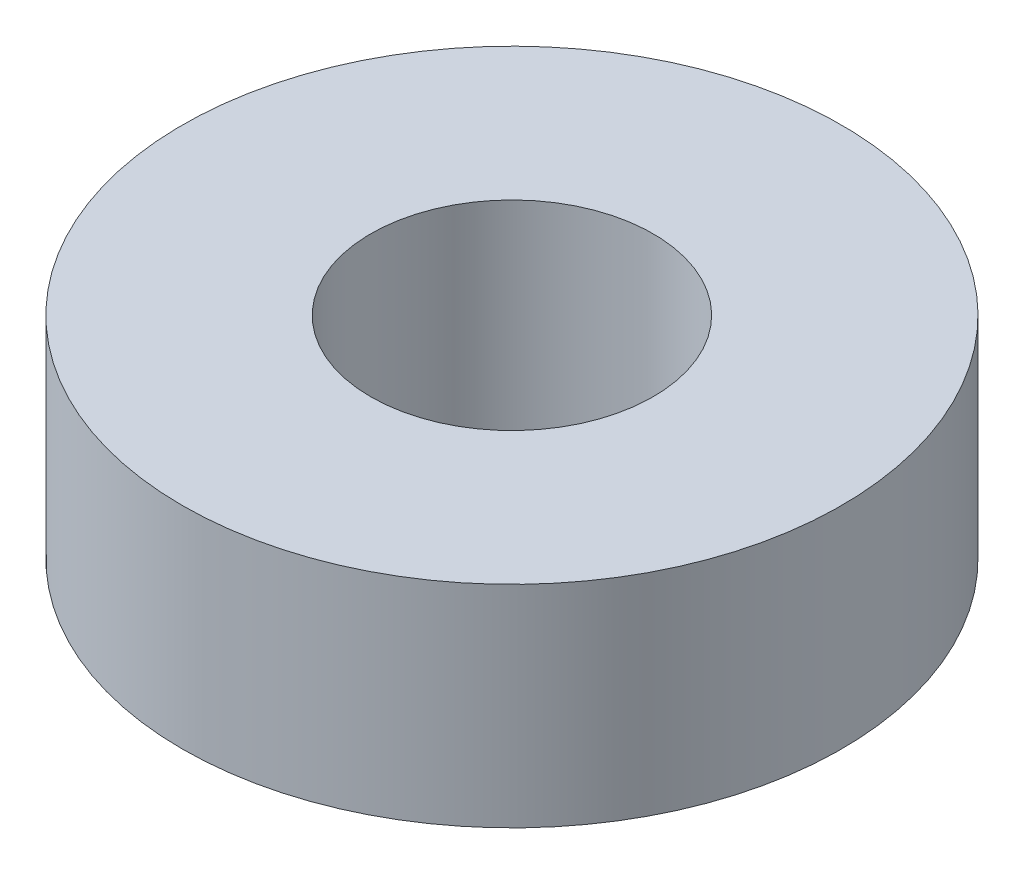
SolidWorks part; units mm, degrees
ref_plane "Front Plane" through (0, 0, 0) normal (0, 0, 1) x (1, 0, 0)
ref_plane "Top Plane" through (0, 0, 0) normal (0, 1, 0) x (1, 0, 0)
ref_plane "Right Plane" through (0, 0, 0) normal (1, 0, 0) x (0, 0, -1)
sketch "Sketch1" plane through (0, 0, 0) normal (0, 1, 0) x (1, 0, 0)
  circle A0 centre (0, 0) radius 11.1125
  circle A1 centre (0, 0) radius 4.7625
extrude "Boss-Extrude1" add sketch "Sketch1" along normal blind 7.112
